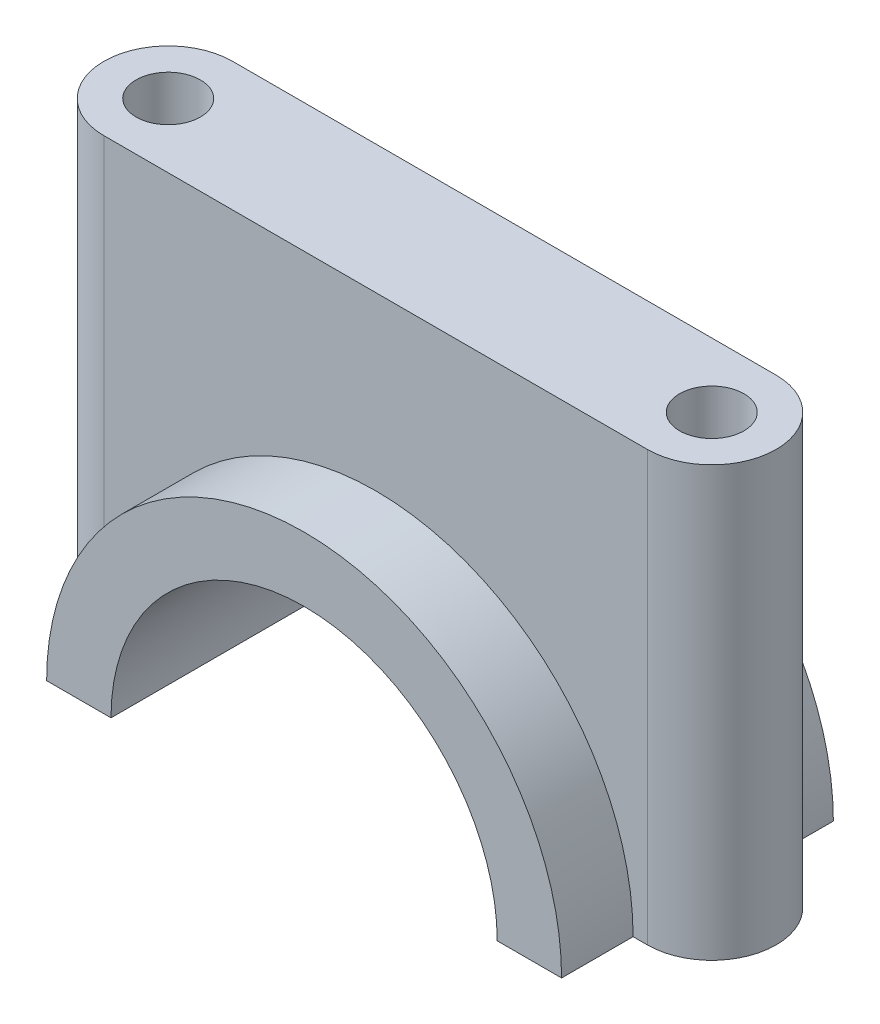
SolidWorks part; units mm, degrees
ref_plane "Front Plane" through (0, 0, 0) normal (0, 0, 1) x (1, 0, 0)
ref_plane "Top Plane" through (0, 0, 0) normal (0, 1, 0) x (1, 0, 0)
ref_plane "Right Plane" through (0, 0, 0) normal (1, 0, 0) x (0, 0, -1)
sketch "Sketch1" plane through (0, 0, 0) normal (0, 0, 1) x (1, 0, 0)
  line L0 (-914.4, 0) -> (-685.8, 0)
  line L1 (685.8, 0) -> (914.4, 0)
  arc A0 (685.8, 0) -> (-685.8, 0) centre (0, 0) ccw
  arc A1 (914.4, 0) -> (-914.4, 0) centre (0, 0) ccw
  dimension "D1" = 1371.6
  dimension "D2" = 1828.8
extrude "Boss-Extrude1" add sketch "Sketch1" along normal mid plane 965.2
ref_plane "Plane1" through (0, 1524, 0) normal (0, -1, 0) x (-1, 0, 0)
sketch "Sketch7" plane through (0, 1524, 0) normal (0, -1, 0) x (-1, 0, 0)
  line L0 (965.2, 0) -> (-965.2, 0) construction
  line L1 (965.2, -228.6) -> (-965.2, -228.6)
  line L2 (965.2, 228.6) -> (-965.2, 228.6)
  arc A0 (965.2, -228.6) -> (965.2, 228.6) centre (965.2, 0) ccw
  arc A1 (-965.2, 228.6) -> (-965.2, -228.6) centre (-965.2, 0) ccw
  point P2 (0, 0)
  dimension "D2" = 228.6
  dimension "D1" = 1930.4
extrude "Boss-Extrude2" add sketch "Sketch7" along normal up to surface (1524 mm away) up to face at (-800.1, 0, 0)
sketch "Sketch8" plane through (0, 0, 228.6) normal (0, 0, 1) x (1, 0, 0)
  line L1 (-685.8, 0) -> (685.8, 0)
  line L2 (-685.8, 0) -> (685.8, 0)
  arc A1 (685.8, 0) -> (-685.8, 0) centre (0, 0) ccw
  arc A2 (685.8, 0) -> (-685.8, 0) centre (0, 0) ccw
  dimension "D1" = 0
extrude "Cut-Extrude2" cut sketch "Sketch8" against normal through all
sketch "Sketch9" plane through (0, 0, 0) normal (0, -1, 0) x (1, 0, 0)
  circle A0 centre (-965.2, 0) radius 114.3
  circle A1 centre (965.2, 0) radius 114.3
  dimension "D1" = 228.6
  dimension "D2" = 228.6
extrude "Cut-Extrude3" cut sketch "Sketch9" against normal through all
